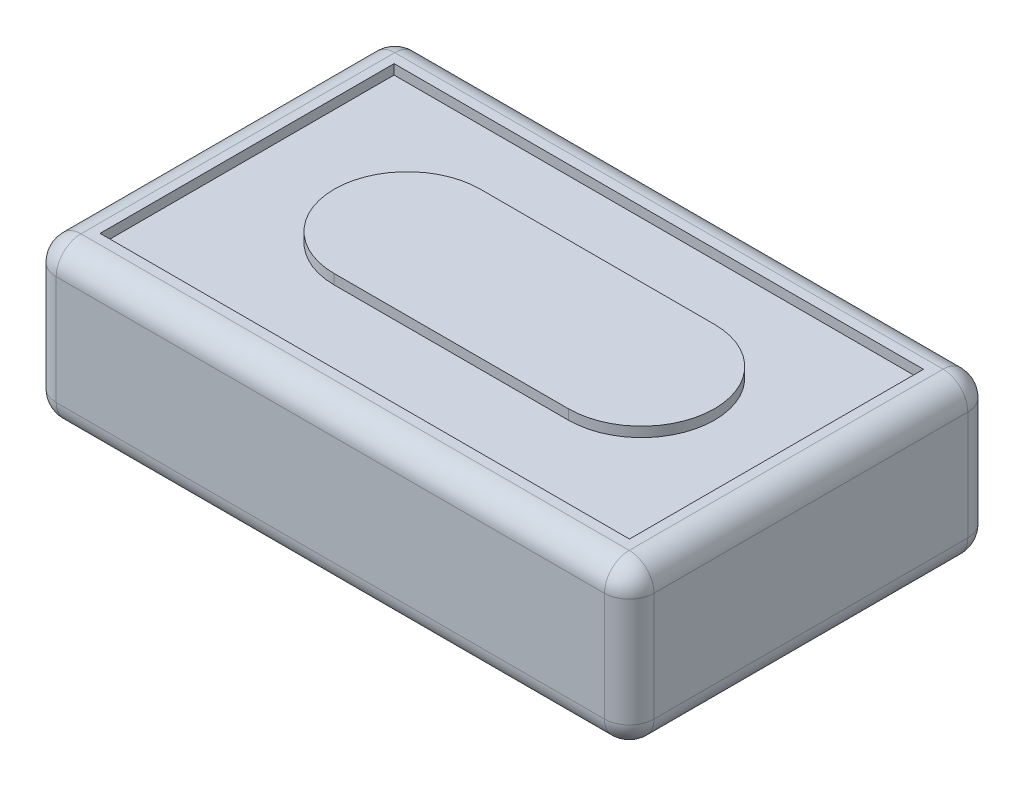
SolidWorks part; units mm, degrees
ref_plane "前视基准面" through (0, 0, 0) normal (0, 0, 1) x (1, 0, 0)
ref_plane "上视基准面" through (0, 0, 0) normal (0, 1, 0) x (1, 0, 0)
ref_plane "右视基准面" through (0, 0, 0) normal (1, 0, 0) x (0, 0, -1)
other "Configuration Table"
sketch "草图1" plane through (0, 0, 0) normal (0, 1, 0) x (1, 0, 0)
  line L1 (-72.8912, 42.6566) -> (47.8129, 42.6566)
  line L2 (-72.8912, 42.6566) -> (-72.8912, -30.7034)
  line L3 (-72.8912, -30.7034) -> (47.8129, -30.7034)
  line L4 (47.8129, 42.6566) -> (47.8129, -30.7034)
extrude "凸台-拉伸1" add sketch "草图1" along normal blind 32 contours L2 L1 L4 L3
fillet "圆角4" radius 5 12 edges at (-72.8912, 32, -5.9766) (-72.8912, 16, 30.7034) (-12.5392, 32, 30.7034) (-72.8912, 0, -5.9766) (-12.5392, 0, 30.7034) (-12.5392, 32, -42.6566) (-72.8912, 16, -42.6566) (-12.5392, 0, -42.6566) (47.8129, 16, 30.7034) (47.8129, 32, -5.9766) (47.8129, 16, -42.6566) (47.8129, 0, -5.9766)
sketch "草图2" plane through (0, 32, 0) normal (0, 1, 0) x (1, 0, 0)
  line L1 (-64.3432, 34.6051) -> (38.9651, 34.6051)
  line L2 (-64.3432, 34.6051) -> (-64.3432, -22.4155)
  line L3 (-64.3432, -22.4155) -> (38.9651, -22.4155)
  line L4 (38.9651, 34.6051) -> (38.9651, -22.4155)
extrude "凸台-拉伸2" add sketch "草图2" against normal blind 1 contours L2 L1 L4 L3
sketch "草图3" plane through (0, 32, 0) normal (0, 1, 0) x (1, 0, 0)
  line L1 (-66.0379, 35.6672) -> (40.8587, 35.6672)
  line L2 (-66.0379, 35.6672) -> (-66.0379, -23.6973)
  line L3 (-66.0379, -23.6973) -> (40.8587, -23.6973)
  line L4 (40.8587, 35.6672) -> (40.8587, -23.6973)
extrude "切除-拉伸1" cut sketch "草图3" against normal blind 2
sketch "草图5" plane through (0, 30, 0) normal (0, 1, 0) x (1, 0, 0)
  line L0 (-35.3749, 7.6698) -> (11.9074, 7.6698) construction
  line L1 (-35.3749, 22.4199) -> (11.9074, 22.4199)
  line L2 (-35.3749, -7.0803) -> (11.9074, -7.0803)
  arc A0 (-35.3749, 22.4199) -> (-35.3749, -7.0803) centre (-35.3749, 7.6698) ccw
  arc A1 (11.9074, -7.0803) -> (11.9074, 22.4199) centre (11.9074, 7.6698) ccw
  point P2 (-11.7337, 7.6698)
extrude "凸台-拉伸4" add sketch "草图5" along normal blind 2 contours L2 A1 L1 A0
sketch "草图6" plane through (0, 0, 0) normal (0, -1, 0) x (1, 0, 0)
  line L1 (-66.154, 23.8032) -> (41.1211, 23.8032)
  line L2 (-66.154, 23.8032) -> (-66.154, -35.7253)
  line L3 (-66.154, -35.7253) -> (41.1211, -35.7253)
  line L4 (41.1211, 23.8032) -> (41.1211, -35.7253)
extrude "切除-拉伸2" cut sketch "草图6" against normal blind 26
